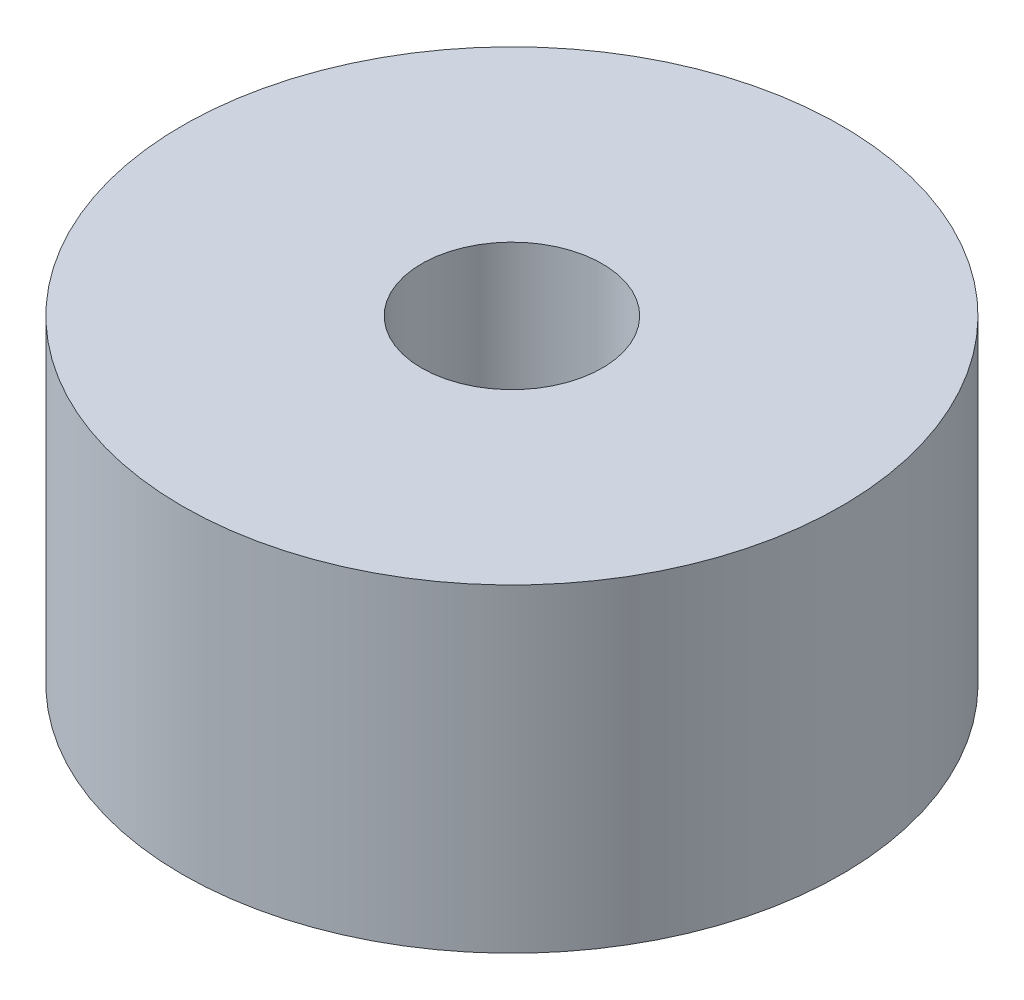
SolidWorks part; units mm, degrees
ref_plane "Спереди" through (0, 0, 0) normal (0, 0, 1) x (1, 0, 0)
ref_plane "Сверху" through (0, 0, 0) normal (0, 1, 0) x (1, 0, 0)
ref_plane "Справа" through (0, 0, 0) normal (1, 0, 0) x (0, 0, -1)
sketch "Эскиз1" plane through (0, 0, 0) normal (0, 1, 0) x (1, 0, 0)
  circle A0 centre (0, 0) radius 4.25
  circle A1 centre (0, 0) radius 15.5
  dimension "D1" = 8.5
  dimension "D2" = 31
extrude "Бобышка-Вытянуть1" add sketch "Эскиз1" along normal blind 15
